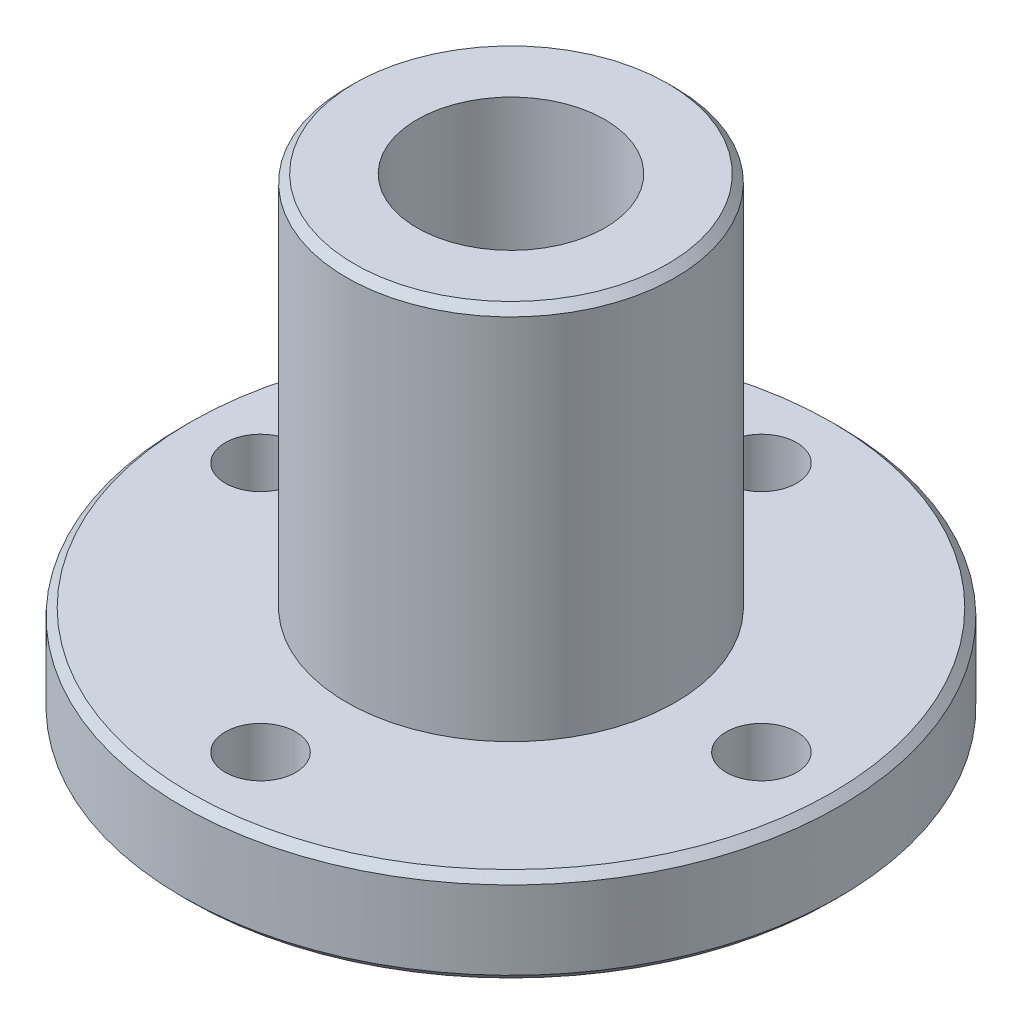
SolidWorks part; units mm, degrees
ref_plane "Front Plane" through (0, 0, 0) normal (0, 0, 1) x (1, 0, 0)
ref_plane "Top Plane" through (0, 0, 0) normal (0, 1, 0) x (1, 0, 0)
ref_plane "Right Plane" through (0, 0, 0) normal (1, 0, 0) x (0, 0, -1)
sketch "Sketch1" plane through (0, 0, 0) normal (0, 0, 1) x (1, 0, 0)
  line L0 (0, 0) -> (0, 15494.3637) construction
  line L1 (0, 0) -> (-21, 0)
  line L2 (-21, 0) -> (-21, 6)
  line L3 (-21, 6) -> (-10.5, 6)
  line L4 (-10.5, 6) -> (-10.5, 30)
  line L5 (-10.5, 30) -> (0, 30)
  line L6 (0, 30) -> (0, 0)
  dimension "D1" = 21
  dimension "D2" = 42
  dimension "D3" = 30
  dimension "D4" = 6
revolve "Revolve1" add sketch "Sketch1" angle 360 about L0
sketch "Sketch2" plane through (0, 0, 0) normal (0, -1, 0) x (1, 0, 0)
  circle A0 centre (0, 0) radius 6
  dimension "D1" = 12
extrude "Cut-Extrude1" cut sketch "Sketch2" against normal through all
sketch "Sketch3" plane through (0, 6, 0) normal (0, 1, 0) x (1, 0, 0)
  circle A0 centre (0, 0) radius 16 construction
  point P3 (0, 16)
  point P4 (0, -16)
  point P5 (16, 0)
  point P6 (-16, 0)
  dimension "D1" = 32
hole_wizard "Отверстие с зазором M41" positions "Sketch4" profile "Sketch5" hole size "M4" standard "ISO"
sketch "Sketch4" plane through (0, 6, 0) normal (0, 1, 0) x (1, 0, 0)
  point P0 (0, 16)
  point P3 (16, 0)
  point P6 (0, -16)
  point P9 (-16, 0)
sketch "Sketch5" plane through (0, 6, -16) normal (1, 0, 0) x (0, 0, 1)
  line L0 (0, 0) -> (0, 23.3519)
  line L1 (0, 23.3519) -> (2.25, 22)
  line L2 (2.25, 22) -> (2.25, 0)
  line L5 (2.25, 0) -> (0, 0)
  line L10 (0, 23.3519) -> (-2.25, 22) construction
  line L11 (0, -6.35) -> (0, 107.95) construction
  dimension "Диаметр отверстия" = 4.5
  dimension "Глубина отверстия" = 22
  dimension "Угол заточки сверла" = 118
chamfer "Chamfer1" distance 0.5 angle 45 3 edges at (0, 30, -10.5) (0, 6, -21) (0, 0, -21)
